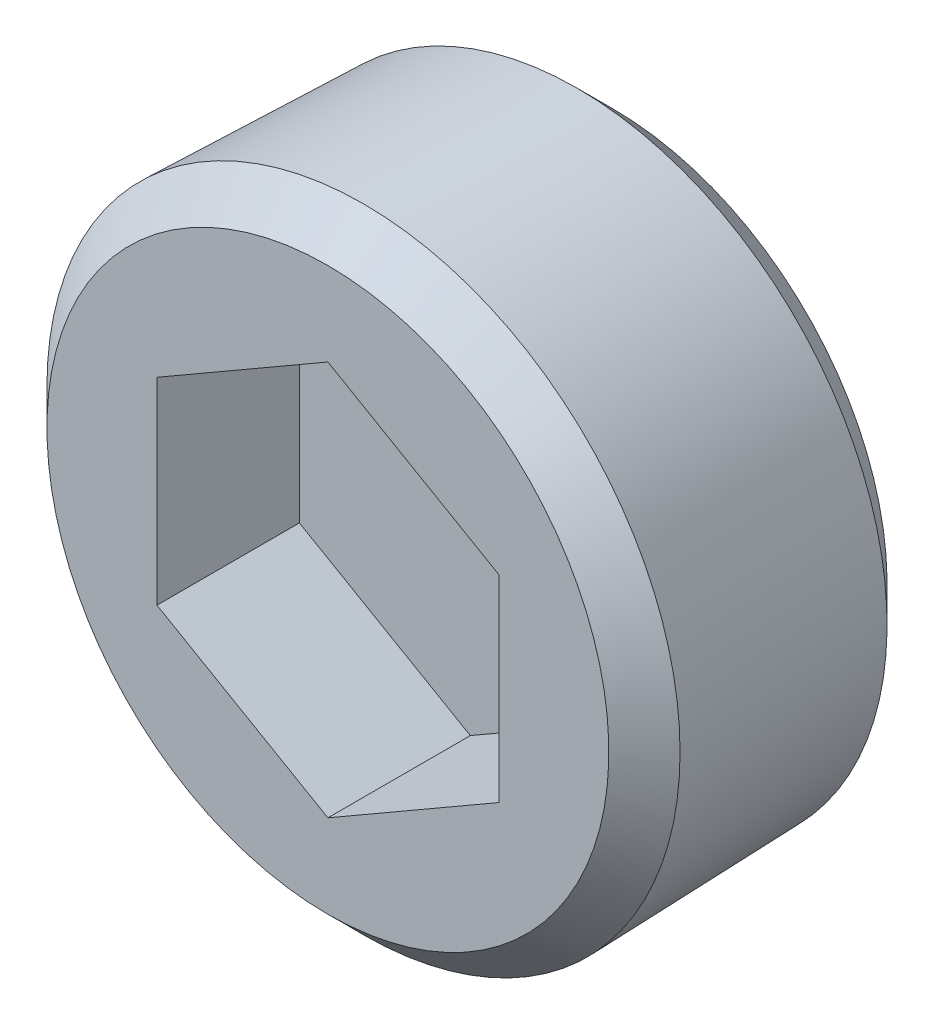
SolidWorks part; units mm, degrees
material "4140 H/T"
ref_plane "Front Plane" through (0, 0, 0) normal (0, 0, 1) x (1, 0, 0)
ref_plane "Top Plane" through (0, 0, 0) normal (0, 1, 0) x (1, 0, 0)
ref_plane "Right Plane" through (0, 0, 0) normal (1, 0, 0) x (0, 0, -1)
sketch "Sketch1" plane through (0, 0, 0) normal (1, 0, 0) x (0, 0, -1)
  line L0 (0, 0) -> (0, 11.5541)
  line L1 (0, 11.5541) -> (-1.5, 13.0541)
  line L2 (-1.5, 13.0541) -> (-10.5, 13.335)
  line L3 (-10.5, 13.335) -> (-12, 11.835)
  line L4 (-12, 11.835) -> (-12, 0)
  line L5 (0, 0) -> (-12, 0) construction
  line L6 (0, 0) -> (-12, 0)
  dimension "D1" = 12
  dimension "D2" = 26.67
  dimension "D3" = 1.788
  dimension "D4" = 1.5
  dimension "D5" = 45
  dimension "D6" = 1.5
  dimension "D7" = 45
revolve "Revolve1" add sketch "Sketch1" angle 360 about L5
cosmetic thread "Cosmetic Thread1" parameters "D2"=23.1269
sketch "Sketch2" plane through (0, 0, 12) normal (0, 0, 1) x (1, 0, 0)
  line L1 (0, -8.3138) -> (7.2, -4.1569)
  line L2 (7.2, -4.1569) -> (7.2, 4.1569)
  line L3 (7.2, 4.1569) -> (0, 8.3138)
  line L4 (0, 8.3138) -> (-7.2, 4.1569)
  line L5 (-7.2, 4.1569) -> (-7.2, -4.1569)
  line L6 (-7.2, -4.1569) -> (0, -8.3138)
  circle A0 centre (0, 0) radius 7.2 construction
  dimension "D1" = 14.4
extrude "Cut-Extrude1" cut sketch "Sketch2" against normal blind 6
